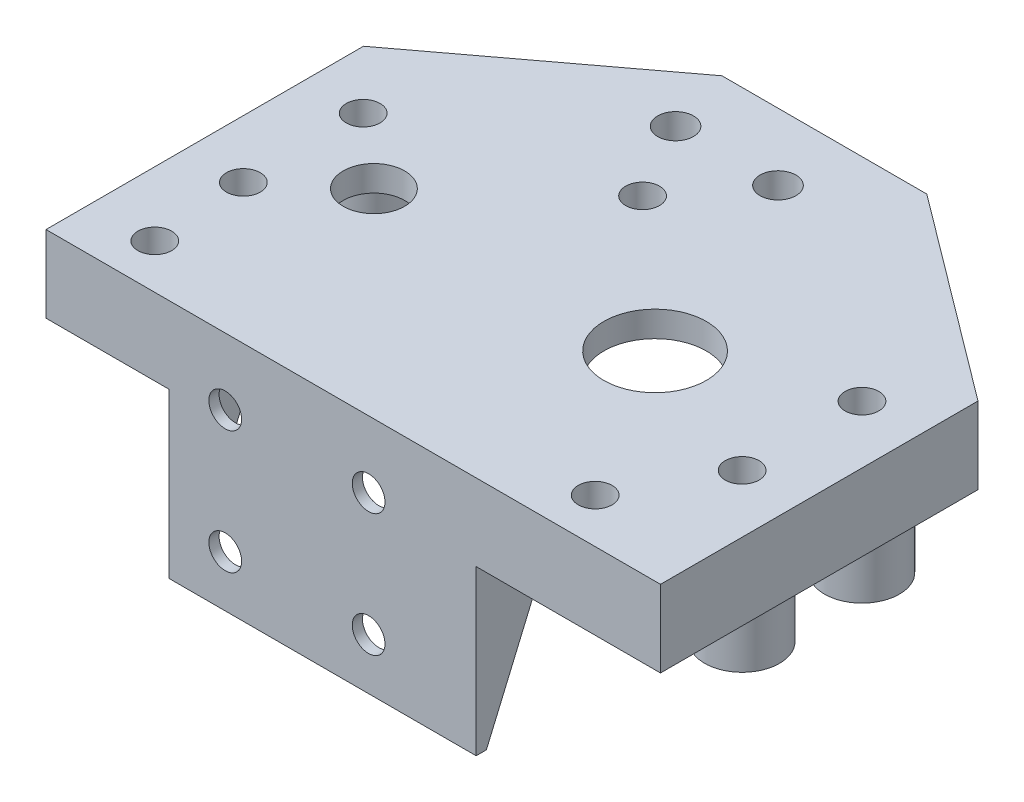
SolidWorks part; units mm, degrees
ref_plane "前视基准面" through (0, 0, 0) normal (0, 0, 1) x (1, 0, 0)
ref_plane "上视基准面" through (0, 0, 0) normal (0, 1, 0) x (1, 0, 0)
ref_plane "右视基准面" through (0, 0, 0) normal (1, 0, 0) x (0, 0, -1)
sketch "草图1" plane through (0, 0, 0) normal (0, 1, 0) x (1, 0, 0)
  line L0 (-15.6401, 19.4698) -> (40.7401, 19.4698) construction
  line L1 (0, 0) -> (60, 0)
  line L2 (0, 0) -> (0, 31)
  line L4 (60, 0) -> (60, 31)
  line L5 (30, 40) -> (30, -2.1076) construction
  line L6 (0, 31) -> (20, 46)
  line L11 (60, 31) -> (40, 46)
  line L12 (20, 46) -> (40, 46)
  circle A0 centre (5.65, 13.6198) radius 1.65
  circle A1 centre (54.35, 13.6198) radius 1.65
  circle A2 centre (5.65, 25.3198) radius 1.65
  circle A3 centre (54.35, 25.3198) radius 1.65
  circle A4 centre (40, 19.4698) radius 5
  circle A5 centre (12.55, 19.4698) radius 3
  circle A6 centre (26.28, 31.9698) radius 1.65
  circle A7 centre (22, 39.4698) radius 1.75
  circle A8 centre (32, 39.4698) radius 1.75
  point P17 (30, 19.4698)
  dimension "D1" = 48.7
  dimension "D2" = 3.3
  dimension "D3" = 11.7
  dimension "D5" = 20
  dimension "D6" = 10
  dimension "D8" = 27.45
  dimension "D9" = 6
  dimension "D12" = 12.5
  dimension "D13" = 3.3
  dimension "D15" = 20
  dimension "D16" = 9.45
  dimension "D17" = 3.5
  dimension "D18" = 10
  dimension "D19" = 3.5
  dimension "D4" = 60
  dimension "D7" = 31
  dimension "D10" = 15
  dimension "D11" = 20
  dimension "D14" = 13.73
extrude "凸台-拉伸1" add sketch "草图1" along normal blind 2.5
sketch "草图2" plane through (0, 0, 0) normal (0, -1, 0) x (1, 0, 0)
  circle A0 centre (5.65, -13.6198) radius 3.65
  circle A1 centre (5.65, -13.6198) radius 1.65
  circle A2 centre (5.65, -25.3198) radius 3.65
  circle A3 centre (5.65, -25.3198) radius 1.65 construction
  circle A4 centre (5.65, -25.3198) radius 1.65
  circle A5 centre (5.65, -13.6198) radius 1.65 construction
  circle A6 centre (54.35, -13.6198) radius 1.65
  circle A7 centre (54.35, -13.6198) radius 3.65
  circle A8 centre (54.35, -25.3198) radius 1.65
  circle A9 centre (54.35, -25.3198) radius 3.65
  dimension "D1" = 2
  dimension "D2" = 2
  dimension "D3" = 2
  dimension "D4" = 2
extrude "凸台-拉伸2" add sketch "草图2" along normal blind 12
sketch "草图4" plane through (0, 0, 0) normal (0, -1, 0) x (1, 0, 0)
  circle A0 centre (22, -39.4698) radius 3.25
  circle A1 centre (22, -39.4698) radius 1.75
  circle A2 centre (32, -39.4698) radius 1.75
  circle A3 centre (32, -39.4698) radius 3.25
  dimension "D1" = 1.5
  dimension "D2" = 1.5
extrude "凸台-拉伸3" add sketch "草图4" along normal blind 2.5
sketch "草图6" plane through (0, 0, 0) normal (0, -1, 0) x (1, 0, 0)
  line L0 (0, -31) -> (20, -46)
  line L1 (20, -46) -> (40, -46)
  line L2 (40, -46) -> (60, -31)
  line L3 (60, -31) -> (60, 0)
  line L4 (60, 0) -> (0, 0)
  line L5 (0, 0) -> (0, -31)
  line L6 (1, -1) -> (1, -30.5)
  line L7 (1, -30.5) -> (20.3333, -45)
  line L8 (20.3333, -45) -> (39.6667, -45)
  line L9 (39.6667, -45) -> (59, -30.5)
  line L10 (59, -30.5) -> (59, -1)
  line L11 (59, -1) -> (1, -1)
  dimension "D1" = 1
extrude "凸台-拉伸5" add sketch "草图6" along normal blind 5
sketch "草图10" plane through (0, 0, 0) normal (0, 0, 1) x (1, 0, 0)
  line L0 (60, -5) -> (0, -5) construction
  line L2 (12, -5) -> (42, -5)
  line L3 (12, -5) -> (12, -21)
  line L4 (12, -21) -> (42, -21)
  line L5 (42, -21) -> (42, -5)
  dimension "D2" = 16
  dimension "D1" = 30
extrude "凸台-拉伸7" add sketch "草图10" against normal blind 1
ref_plane "基准面2" through (24, 0, 0) normal (-1, 0, 0) x (0, 0, 1)
sketch "草图11" plane through (24, 0, 0) normal (-1, 0, 0) x (0, 0, 1)
  line L0 (-1, -21) -> (-1, 0)
  line L1 (-1, 0) -> (-9.9698, 0)
  line L2 (-9.9698, 0) -> (-1, -21)
extrude "凸台-拉伸8" add sketch "草图11" along normal mid plane 1
sketch "草图12" plane through (12, 0, 0) normal (-1, 0, 0) x (0, 0, 1)
  line L0 (-1, -21) -> (-1, 0)
  line L1 (-1, 0) -> (-9.9698, 0)
  line L2 (-9.9698, 0) -> (-1, -21)
extrude "凸台-拉伸9" add sketch "草图12" against normal blind 1
sketch "草图13" plane through (42, 0, 0) normal (1, 0, 0) x (0, 0, -1)
  line L0 (1, -21) -> (9.9698, 0)
  line L1 (30.5, 0) -> (1, 0) construction
  line L2 (9.9698, 0) -> (1, -21) construction
  line L3 (9.9698, 0) -> (1, 0)
  line L4 (1, 0) -> (1, -21)
  line L5 (1, -5) -> (1, 0) construction
extrude "凸台-拉伸10" add sketch "草图13" against normal blind 1
sketch "草图15" plane through (0, 0, 0) normal (0, 0, 1) x (1, 0, 0)
  line L1 (12, -5) -> (12, -21) construction
  line L2 (12, -21) -> (42, -21) construction
  circle A0 centre (17.5, -16) radius 1.6
  circle A1 centre (17.5, -4) radius 1.6
  circle A2 centre (31.5, -16) radius 1.6
  circle A3 centre (31.5, -4) radius 1.6
  dimension "D1" = 14
  dimension "D2" = 3.2
  dimension "D3" = 5
  dimension "D4" = 12
  dimension "D5" = 3.2
  dimension "D7" = 5.5
  dimension "D6" = 12
  dimension "D8" = 5
extrude "切除-拉伸1" cut sketch "草图15" against normal blind 1
sketch "草图16" plane through (0, 2.5, 0) normal (0, 1, 0) x (1, 0, 0)
  line L0 (0, 0) -> (60, 0) construction
  line L1 (0, 31) -> (0, 0) construction
  circle A0 centre (6.27, 4.35) radius 1.65
  circle A1 centre (49.27, 4.35) radius 1.65
  point P8 (0, 0)
  dimension "D1" = 4.35
  dimension "D2" = 6.27
  dimension "D3" = 3.3
  dimension "D4" = 43
extrude "切除-拉伸2" cut sketch "草图16" against normal blind 10
